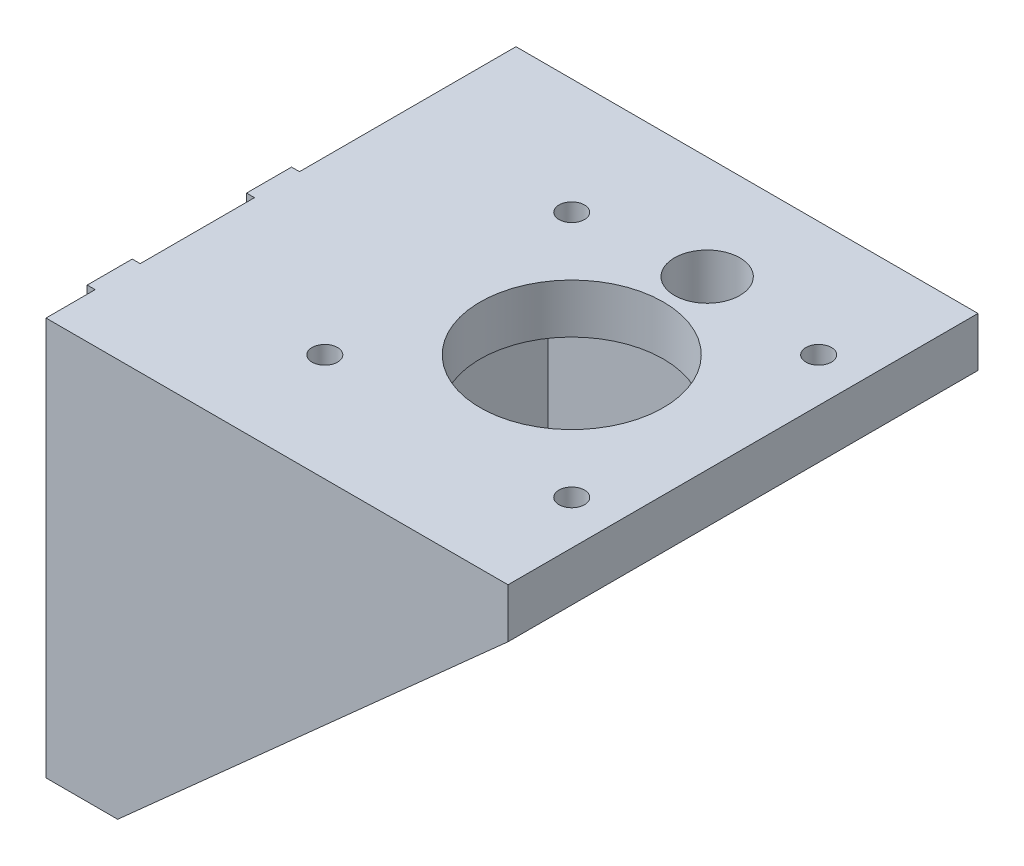
SolidWorks part; units mm, degrees
ref_plane "Plano frontal" through (0, 0, 0) normal (0, 0, 1) x (1, 0, 0)
ref_plane "Plano superior" through (0, 0, 0) normal (0, 1, 0) x (1, 0, 0)
ref_plane "Plano direito" through (0, 0, 0) normal (1, 0, 0) x (0, 0, -1)
sketch "Esboço1" plane through (0, 0, 0) normal (0, 0, 1) x (1, 0, 0)
  line L0 (9, 0) -> (58, 43.8)
  line L1 (0, 50) -> (58, 50)
  line L2 (0, 50) -> (0, 0)
  line L3 (0, 0) -> (9, 0)
  line L4 (58, 50) -> (58, 43.8)
  point P0 (0, 0)
  dimension "D1" = 58
  dimension "D2" = 9
  dimension "D3" = 6.2
  dimension "D4" = 50
extrude "Ressalto-extrusão1" add sketch "Esboço1" along normal blind 59
sketch "Esboço2" plane through (58, 0, 0) normal (1, 0, 0) x (0, 0, -1)
  line L0 (-54, 43.8) -> (-4, 43.8)
  line L1 (-59, 43.8) -> (0, 43.8) construction
  line L2 (-4, 43.8) -> (-4, 0)
  line L3 (-59, 0) -> (0, 0) construction
  line L4 (-4, 0) -> (-54, 0)
  line L5 (-54, 0) -> (-54, 43.8)
  line L6 (-59, 0) -> (-59, 43.8) construction
  line L7 (0, 0) -> (0, 43.8) construction
  dimension "D1" = 5
  dimension "D2" = 4
extrude "Corte-extrusão1" cut sketch "Esboço2" against normal offset from surface (49 mm away) 9 up to face at (0, 25, 29.5)
sketch "Esboço3" plane through (9, 0, 0) normal (1, 0, 0) x (0, 0, -1)
  line L0 (-29, 31.9) -> (-29, 11.9) construction
  line L3 (-59, 0) -> (-59, 43.8) construction
  line L4 (-59, 21.9) -> (0, 21.9) construction
  line L5 (0, 0) -> (0, 43.8) construction
  line L6 (-29, 0) -> (-29, 7.3672) construction
  line L7 (-4, 0) -> (-54, 0) construction
  line L8 (-9, 31.9) -> (-9, 11.9) construction
  circle A0 centre (-29, 11.9) radius 1.75
  circle A1 centre (-29, 31.9) radius 1.75
  circle A2 centre (-9, 31.9) radius 1.75
  circle A3 centre (-9, 11.9) radius 1.75
  point P0 (-29, 21.9)
  point P22 (-9, 21.9)
  dimension "D1" = 3.5
  dimension "D2" = 20
  dimension "D3" = 20
extrude "Corte-extrusão2" cut sketch "Esboço3" against normal through all
sketch "Esboço4" plane through (0, 0, 0) normal (-1, 0, 0) x (0, 0, 1)
  line L0 (6.175, 50) -> (6.175, 0)
  line L1 (59, 50) -> (0, 50) construction
  line L2 (59, 0) -> (0, 0) construction
  line L3 (6.175, 0) -> (11.825, 0)
  line L4 (11.825, 0) -> (11.825, 50)
  line L5 (11.825, 50) -> (6.175, 50)
  line L6 (9, 50) -> (9, 0) construction
  line L7 (26.175, 50) -> (26.175, 0)
  line L8 (26.175, 0) -> (31.825, 0)
  line L9 (31.825, 0) -> (31.825, 50)
  line L10 (31.825, 50) -> (26.175, 50)
  line L11 (29, 50) -> (29, 0) construction
  circle A0 centre (9, 31.9) radius 1.75 construction
  circle A1 centre (9, 31.9) radius 1.75 construction
  circle A2 centre (29, 31.9) radius 1.75 construction
  circle A3 centre (29, 31.9) radius 1.75 construction
  circle M13 centre (9, 11.9) radius 1.75
  circle M14 centre (9, 31.9) radius 1.75
  circle M15 centre (29, 31.9) radius 1.75
  circle M16 centre (29, 11.9) radius 1.75
  line M18 (0, 0) -> (59, 0)
  line M20 (59, 50) -> (0, 50)
  dimension "D1" = 5.65
  dimension "D2" = 5.65
extrude "Ressalto-extrusão2" add sketch "Esboço4" along normal blind 1 contours L4 L0 M18 M20 M13 M14 | L9 L7 M18 M20 M16 M15
sketch "Esboço5" plane through (9, 0, 0) normal (1, 0, 0) x (0, 0, -1)
  circle A0 centre (-29, 31.9) radius 4.35
  circle A1 centre (-9, 31.9) radius 4.35
  circle A2 centre (-29, 11.9) radius 4.35
  circle A3 centre (-9, 11.9) radius 4.35
  dimension "D1" = 8.7
extrude "Corte-extrusão3" cut sketch "Esboço5" against normal blind 4
sketch "Esboço6" plane through (0, 50, 0) normal (0, 1, 0) x (1, 0, 0)
  line L0 (58, 0) -> (0, 0) construction
  line L1 (58, -59) -> (58, 0) construction
  line L3 (52.5, -44.5) -> (21.5, -44.5) construction
  line L4 (52.5, -44.5) -> (52.5, -13.5) construction
  line L5 (52.5, -13.5) -> (21.5, -13.5) construction
  line L6 (21.5, -44.5) -> (21.5, -13.5) construction
  line L7 (52.5, -44.5) -> (21.5, -13.5) construction
  line L8 (52.5, -13.5) -> (21.5, -44.5) construction
  line L9 (37, -29) -> (37, -46) construction
  circle A0 centre (37, -29) radius 11.5
  circle A1 centre (21.5, -13.5) radius 1.6
  circle A2 centre (52.5, -13.5) radius 1.6
  circle A3 centre (52.5, -44.5) radius 1.6
  circle A4 centre (21.5, -44.5) radius 1.6
  circle A5 centre (37, -46) radius 4.1
  dimension "D3" = 23
  dimension "D6" = 3.2
  dimension "D7" = 8.2
  dimension "D1" = 29
  dimension "D2" = 21
  dimension "D4" = 31
  dimension "D5" = 31
  dimension "D8" = 17
extrude "Corte-extrusão4" cut sketch "Esboço6" against normal up to surface (6.2 mm away) up to face at (33.5, 43.8, 29)
ref_plane "Plano1" through (0, 0, -10) normal (0, 0, -1) x (-1, 0, 0)
mirror "Espelhar2" about plane through (0, 0, -10) normal (0, 0, -1) of bodies 106
sketch "Esboço7" plane through (0, 0, -10) normal (0, 0, -1) x (-1, 0, 0)
  line L1 (55.3406, 71.8005) -> (-91.3044, 71.8005)
  line L2 (55.3406, 71.8005) -> (55.3406, -23.6794)
  line L3 (55.3406, -23.6794) -> (-91.3044, -23.6794)
  line L4 (-91.3044, 71.8005) -> (-91.3044, -23.6794)
  line L5 (55.3406, 71.8005) -> (-91.3044, -23.6794) construction
  line L6 (55.3406, -23.6794) -> (-91.3044, 71.8005) construction
  point P0 (-17.9819, 24.0605)
extrude "Corte-extrusão5" cut sketch "Esboço7" against normal blind 139
equation "\"`9\"=10.8324"
